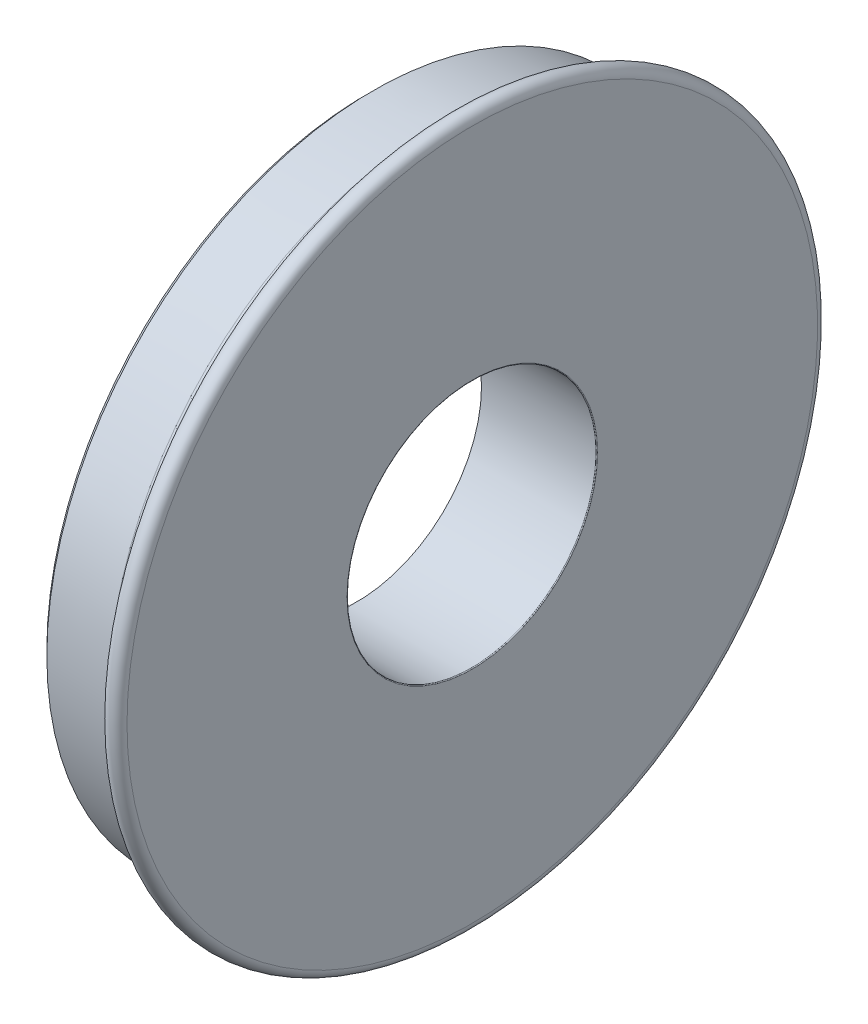
SolidWorks part; units mm, degrees
material "Cast Alloy Steel"
ref_plane "Front Plane" through (0, 0, 0) normal (0, 0, 1) x (1, 0, 0)
ref_plane "Top Plane" through (0, 0, 0) normal (0, 1, 0) x (1, 0, 0)
ref_plane "Right Plane" through (0, 0, 0) normal (1, 0, 0) x (0, 0, -1)
ref_axis "Wheelset axis" through (-146.1647, 0, 0) along (1, 0, 0)
sketch "Sketch1" plane through (0, 0, 0) normal (0, 0, 1) x (1, 0, 0)
  line L0 (0, 37.8) -> (34.75, 37.8)
  line L1 (35, 38.05) -> (35, 104.8706)
  line L4 (-146.1647, 0) -> (223.6526, 0) construction
  line L6 (29.4345, 105.3086) -> (29.2384, 104.0709)
  line L9 (3.3, 79.4167) -> (13.3, 79.4167)
  line L10 (13.3, 79.4167) -> (13.3, 49.14)
  line L11 (13.3, 49.14) -> (0, 49.14)
  line L12 (0, 49.14) -> (0, 37.8)
  line L13 (3.3, 79.4167) -> (3.3, 97.5167)
  line L14 (4.9579, 99.1746) -> (24.4745, 99.8562)
  line L15 (28.5937, 100) -> (3.3, 100) construction
  line L16 (3.3, 97.5167) -> (4.9579, 99.1746)
  arc A0 (34.75, 37.8) -> (35, 38.05) centre (34.75, 38.05) ccw
  arc A1 (29.2384, 104.0709) -> (24.4745, 99.8562) centre (24.3, 104.8531) cw
  arc A2 (29.4345, 105.3086) -> (35, 104.8706) centre (32.2, 104.8706) cw
  point P19 (3.3, 99.1167)
  dimension "D2" = 0.25
  dimension "D13" = 5
  dimension "D15" = 2.8
  dimension "D1" = 37.8
  dimension "D3" = 31.7
  dimension "D4" = 3.3
  dimension "D5" = 11.34
  dimension "D6" = 10
  dimension "D7" = 19.7
  dimension "D8" = 9
  dimension "D9" = 2
  dimension "D10" = 1.6
  dimension "D11" = 45
  dimension "D12" = 100
  dimension "D14" = 10.7
revolve "Revolve1" add sketch "Sketch1" angle 360 about axis through (-146.1647, 0, 0) along (1, 0, 0)
